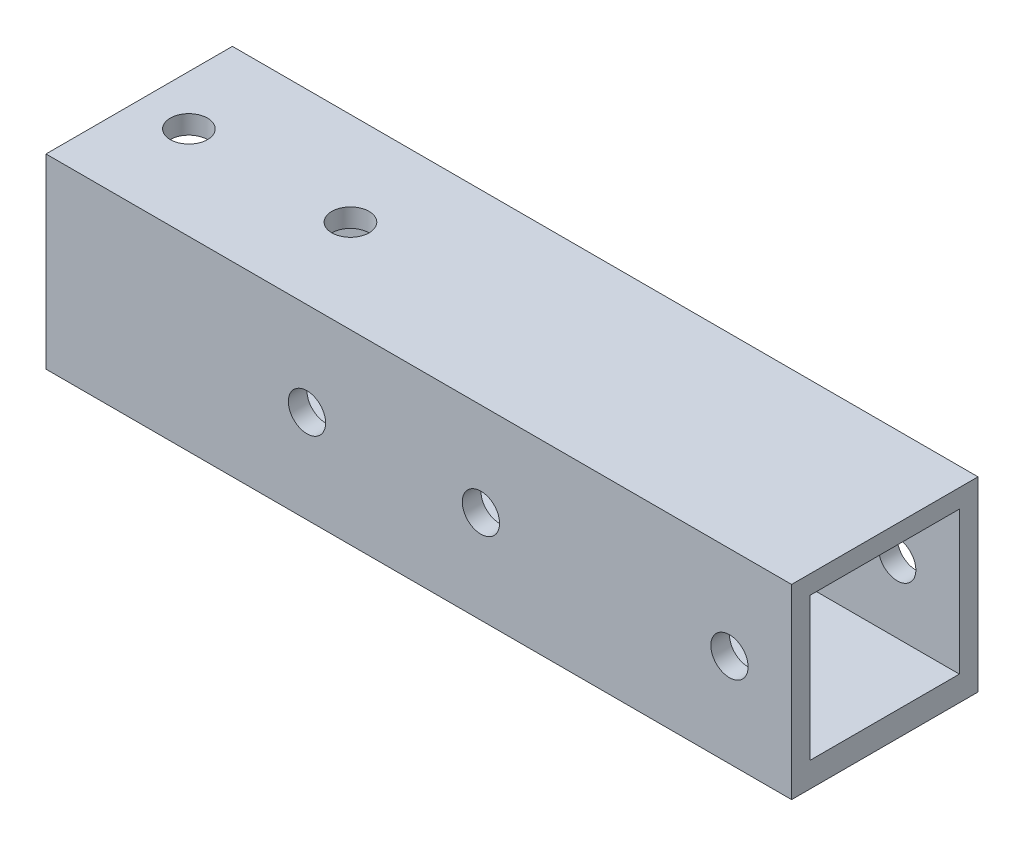
SolidWorks part; units mm, degrees
material "6061 合金"
ref_plane "前视基准面" through (0, 0, 0) normal (0, 0, 1) x (1, 0, 0)
ref_plane "上视基准面" through (0, 0, 0) normal (0, 1, 0) x (1, 0, 0)
ref_plane "右视基准面" through (0, 0, 0) normal (1, 0, 0) x (0, 0, -1)
sketch "草图1" plane through (0, 0, 0) normal (0, 0, 1) x (1, 0, 0)
  line L0 (0, 0) -> (60, 0)
  dimension "D1" = 60
other "方形管 15 ×15× 1.5(1)"
ref_plane "基准面1" through (0, 0, 0) normal (1, 0, 0) x (0, 1, 0)
sketch "Sketch1" plane through (0, 0, 0) normal (1, 0, 0) x (0, 1, 0)
  line L0 (-4, -6) -> (4, -6)
  line L1 (-5.5, -3.5) -> (-5.5, 3.5)
  line L2 (3.5, 6) -> (-3.5, 6)
  line L3 (6, 3.5) -> (6, -3.5)
  line L4 (-6, -7.5) -> (6, -7.5)
  line L5 (-7.5, -6) -> (-7.5, 6)
  line L6 (6, 7.5) -> (-6, 7.5)
  line L7 (7.5, 6) -> (7.5, -6)
  line L8 (-5.5, 3.5) -> (-5.5, 6)
  line L9 (-5.5, 6) -> (-3.5, 6)
  line L10 (-7.5, 6) -> (-7.5, 7.5)
  line L11 (-7.5, 7.5) -> (-6, 7.5)
  line L12 (6, 7.5) -> (7.5, 7.5)
  line L13 (7.5, 7.5) -> (7.5, 6)
  line L14 (3.5, 6) -> (6, 6)
  line L15 (6, 6) -> (6, 3.5)
  line L16 (4, -6) -> (6, -6)
  line L17 (6, -6) -> (6, -3.5)
  line L18 (7.5, -6) -> (7.5, -7.5)
  line L19 (7.5, -7.5) -> (6, -7.5)
  line L20 (-5.5, -3.5) -> (-5.5, -6)
  line L21 (-5.5, -6) -> (-4, -6)
  line L22 (-7.5, -6) -> (-7.5, -7.5)
  line L23 (-7.5, -7.5) -> (-6, -7.5)
  line L24 (0, 7.5) -> (0, -7.5) construction
  line L25 (-7.5, 0) -> (7.5, 0) construction
  point P0 (-7.5, 0)
  point P1 (7.5, 0)
  point P2 (0, 7.5)
  point P3 (0, -7.5)
  point P4 (0, 0)
  point P5 (-7.5, -7.5)
  point P6 (7.5, -7.5)
  point P7 (7.5, 7.5)
  point P8 (-7.5, 7.5)
  point P38 (6, 0)
  point P39 (-5.5, 0)
  point P40 (0, 6)
  point P41 (0, -6)
  point P42 (0, 0)
  dimension "D1" = 1.5
  dimension "D2" = 1.5
  dimension "D3" = 1.5
  dimension "D4" = 1.5
  dimension "D5" = 1.5
  dimension "D6" = 12
  dimension "D7" = 1.5
  dimension "D8" = 1.5
  dimension "Thickness" = 2
  dimension "D9" = 1.5
  dimension "D10" = 1.5
sketch "草图3" plane through (0, 7.5, 0) normal (0, 1, 0) x (1, 0, 0)
  line L0 (0, 0) -> (17, 0) construction
  circle A0 centre (17, 0) radius 1.5
  circle A1 centre (4, 0) radius 1.5
  dimension "D1" = 3
  dimension "D3" = 13
  dimension "D2" = 17
extrude "切除-拉伸1" cut sketch "草图3" against normal through all
sketch "草图5" plane through (0, 0, 7.5) normal (0, 0, 1) x (1, 0, 0)
  line L0 (0, 0) -> (60, 0) construction
  line L1 (60, 7.5) -> (60, -7.5) construction
  circle A0 centre (55, 0) radius 1.5
  circle A1 centre (35, 0) radius 1.5
  dimension "D1" = 20
  dimension "D3" = 3
  dimension "D2" = 5
extrude "切除-拉伸2" cut sketch "草图5" against normal through all
sketch "草图6" plane through (0, 0, -7.5) normal (0, 0, -1) x (-1, 0, 0)
  line L0 (0, 0) -> (-21, 0) construction
  circle A0 centre (-21, 0) radius 1.5
  dimension "D2" = 3
  dimension "D1" = 21
extrude "切除-拉伸3" cut sketch "草图6" against normal through all
